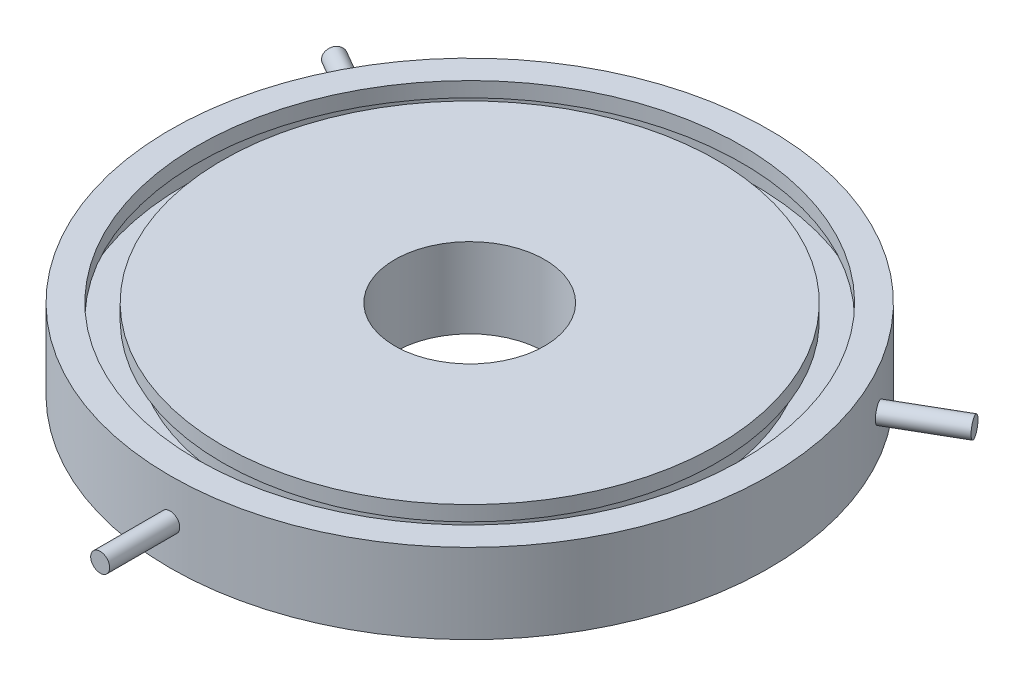
SolidWorks part; units mm, degrees
ref_plane "Front Plane" through (0, 0, 0) normal (0, 0, 1) x (1, 0, 0)
ref_plane "Top Plane" through (0, 0, 0) normal (0, 1, 0) x (1, 0, 0)
ref_plane "Right Plane" through (0, 0, 0) normal (1, 0, 0) x (0, 0, -1)
sketch "Sketch1" plane through (0, 0, 0) normal (0, 1, 0) x (1, 0, 0)
  line L0 (4.1246, 5.7107) -> (4.1191, 5.7052)
  line L1 (-1.1215, 6.9546) -> (-1.1215, 6.9469)
  line L2 (2.7492, 4.0281) -> (2.7453, 4.0242)
  line L3 (-0.9512, 4.9055) -> (-0.9512, 4.9)
  line L4 (-1.1215, 6.9469) -> (-1.1157, 6.9555) construction
  line L6 (6.9546, 1.1215) -> (6.9469, 1.1215)
  line L7 (-0.9512, 7.3073) -> (-0.1429, 6.1027) construction
  line L8 (5.7107, -4.1246) -> (5.7052, -4.1191)
  line L9 (-0.9512, 4.9) -> (0.6641, 7.3036) construction
  line L10 (1.1215, -6.9546) -> (1.1215, -6.9469)
  line L12 (-4.1246, -5.7107) -> (-4.1191, -5.7052)
  line L13 (4.7453, 0.7911) -> (4.7399, 0.7911)
  line L14 (-6.9546, -1.1215) -> (-6.9469, -1.1215)
  line L16 (-5.7107, 4.1246) -> (-5.7052, 4.1191)
  line L17 (3.8679, -2.9093) -> (3.8641, -2.9054)
  line L23 (-5.0656, -0.7911) -> (-5.0601, -0.7911)
  line L25 (-4.1882, 2.9093) -> (-4.1843, 2.9054)
  arc A1 (-1.1157, 6.9555) -> (-1.1215, 6.9546) centre (0, 0) ccw
  circle A2 centre (0, 0) radius 30
  circle A5 centre (0, 0) radius 7.5
  arc A6 (-0.9471, 4.9061) -> (-0.9512, 4.9055) centre (-0.1601, 0) ccw
  point P2 (0.0244, 8.652)
  point P9 (-0.1429, 6.1027)
  point P36 (0, 0)
  point P58 (-0.1601, 0)
  dimension "D1" = 60
  dimension "D2" = 15
extrude "Boss-Extrude1" add sketch "Sketch1" along normal mid plane 8
sketch "Sketch2" plane through (0, 0, 0) normal (1, 0, 0) x (0, 0, -1)
  line L0 (-30, 4) -> (-30, -4) construction
  line L1 (-27.25, 4) -> (-24.75, 4)
  line L2 (-28.5, 2.5) -> (-28.5, -0.04)
  line L3 (-28.5, -0.04) -> (-23.5, -0.04)
  line L4 (-23.5, 2.5) -> (-23.5, -0.04)
  line L5 (-27.25, 2.99) -> (-23.5, -0.04) construction
  line L6 (-28.5, -0.04) -> (-24.75, 2.99) construction
  line L7 (0, 8.26) -> (0, -10.2749) construction
  line L8 (-27.25, 4) -> (-27.25, 2.5)
  line L9 (-27.25, 2.5) -> (-28.5, 2.5)
  line L10 (-26, 4) -> (-26, -0.04) construction
  line L11 (-24.75, 2.5) -> (-23.5, 2.5)
  line L12 (-24.75, 4) -> (-24.75, 2.5)
  point P0 (-26, 1.98)
  dimension "D1" = 1.5
  dimension "D2" = 5
  dimension "D3" = 2.5
  dimension "D4" = 2.54
  dimension "D5" = 1.5
revolve "Cut-Revolve2" cut sketch "Sketch2" angle 360 about L7
sketch "Sketch3" plane through (0, 0, 0) normal (0, 0, 1) x (1, 0, 0)
  circle A0 centre (0, 0) radius 0.95
  circle A1 centre (0, 0) radius 2
  dimension "D1" = 4
  dimension "D2" = 1.9
extrude "Boss-Extrude2" add sketch "Sketch3" along normal blind 8 from offset 29 contours A0
pattern_circular "CirPattern1" count 3 over 360 about axis through (0, 0, 0) along (0, 1, 0) of "Boss-Extrude2"
